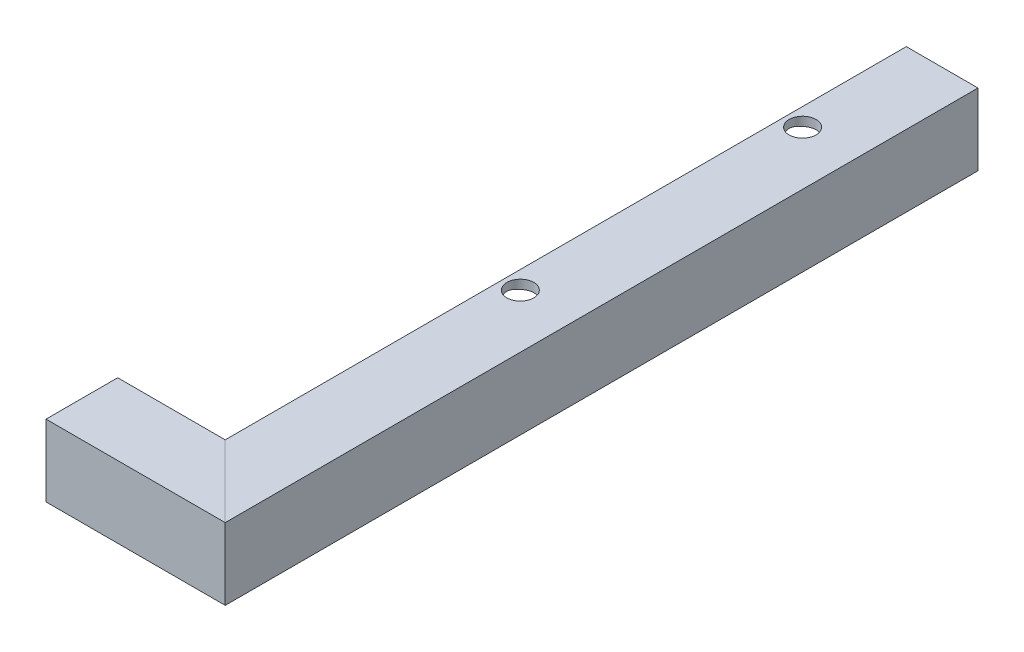
SolidWorks part; units mm, degrees
ref_plane "Alzado" through (0, 0, 0) normal (0, 0, 1) x (1, 0, 0)
ref_plane "Planta" through (0, 0, 0) normal (0, 1, 0) x (1, 0, 0)
ref_plane "Vista lateral" through (0, 0, 0) normal (1, 0, 0) x (0, 0, -1)
sketch3d "Croquis3D1"
  line L0 (0, 0, 0) -> (127, 0, 0)
  line L1 (127, 0, 0) -> (127, 0, -533.4)
  dimension "D1" = 533.4
  dimension "D2" = 127
other "Hierro angular 2 X 2 X 0.125(1)"
ref_plane "Plano3" through (0, 0, 0) normal (1, 0, 0) x (0, -1, 0)
sketch "Sketch1" plane through (0, 0, 0) normal (1, 0, 0) x (0, -1, 0)
  line L0 (0, 0) -> (0, 50.8)
  line L1 (0, 50.8) -> (0.0051, 50.8)
  line L2 (6.35, 44.4551) -> (6.35, 11.1125)
  line L3 (11.1125, 6.35) -> (44.4551, 6.35)
  line L4 (50.8, 0.0051) -> (50.8, 0)
  line L5 (50.8, 0) -> (0, 0)
  arc A0 (50.8, 0.0051) -> (44.4551, 6.35) centre (44.4551, 0.0051) ccw
  arc A1 (0.0051, 50.8) -> (6.35, 44.4551) centre (0.0051, 44.4551) cw
  arc A2 (11.1125, 6.35) -> (6.35, 11.1125) centre (11.1125, 11.1125) cw
  point P10 (25.4, 0)
  point P14 (0, 25.4)
  point P15 (6.35, 25.4)
  point P16 (25.4, 6.35)
  point P17 (6.35, 50.8)
  point P18 (50.8, 6.35)
  point P19 (0, 0)
  dimension "D2" = 0.0051
  dimension "Radius_1" = 4.7625
  dimension "D1" = 6.35
  dimension "H_leg" = 50.8
sketch "Croquis6" plane through (0, 0, 0) normal (0, 1, 0) x (1, 0, 0)
  line L0 (76.2, 533.4) -> (127, 533.4) construction
  line L1 (76.2, 533.4) -> (76.2, 50.8) construction
  circle A0 centre (88.9, 447.2) radius 9.525
  circle A1 centre (88.9, 247.2) radius 9.525
  dimension "D2" = 86.2
  dimension "D4" = 19.05
  dimension "D1" = 200
  dimension "D3" = 12.7
extrude "Cortar-Extruir1" cut sketch "Croquis6" against normal through all
